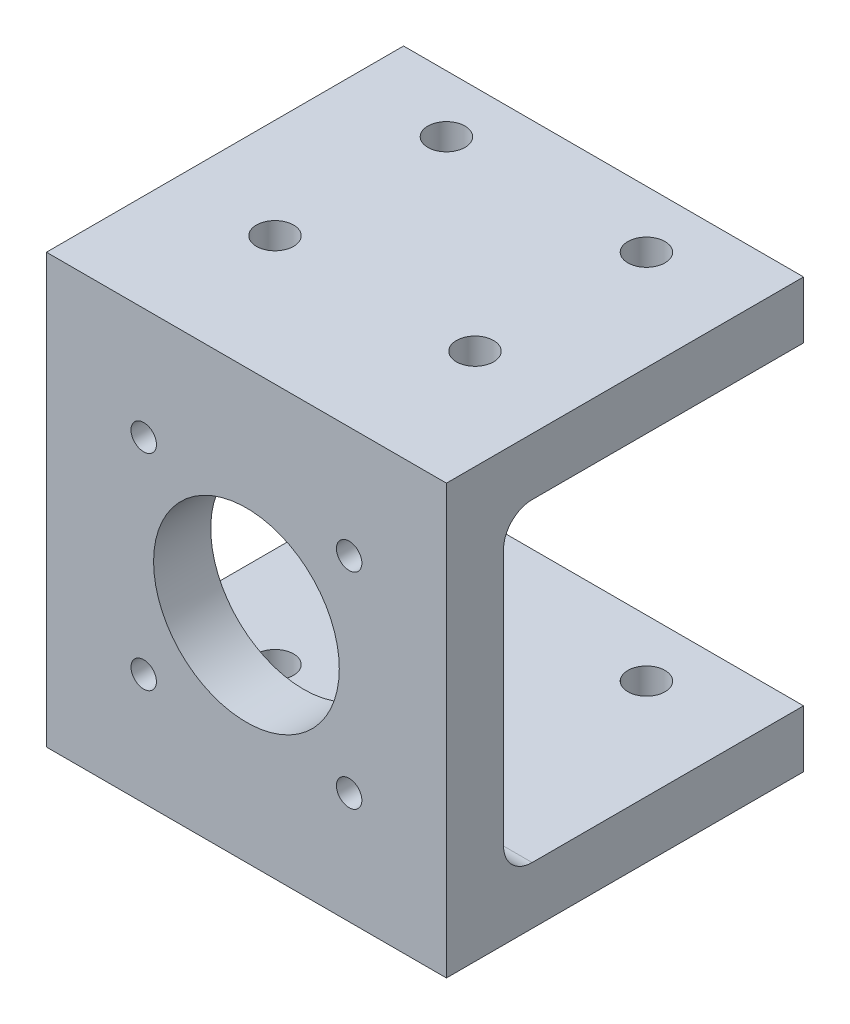
SolidWorks part; units mm, degrees
material "ABS"
ref_plane "Front Plane" through (0, 0, 0) normal (0, 0, 1) x (1, 0, 0)
ref_plane "Top Plane" through (0, 0, 0) normal (0, 1, 0) x (1, 0, 0)
ref_plane "Right Plane" through (0, 0, 0) normal (1, 0, 0) x (0, 0, -1)
sketch "Sketch1" plane through (0, 0, 0) normal (0, 0, 1) x (1, 0, 0)
  line L1 (-17.78, -19.05) -> (17.78, -19.05)
  line L2 (-17.78, -19.05) -> (-17.78, 19.05)
  line L3 (-17.78, 19.05) -> (17.78, 19.05)
  line L4 (17.78, -19.05) -> (17.78, 19.05)
  line L5 (-17.78, -19.05) -> (17.78, 19.05) construction
  line L6 (-17.78, 19.05) -> (17.78, -19.05) construction
  line L7 (-9.1313, -9.1313) -> (9.1313, -9.1313) construction
  line L8 (-9.1313, -9.1313) -> (-9.1313, 9.1313) construction
  line L9 (-9.1313, 9.1313) -> (9.1313, 9.1313) construction
  line L10 (9.1313, -9.1313) -> (9.1313, 9.1313) construction
  line L11 (-9.1313, -9.1313) -> (9.1313, 9.1313) construction
  line L12 (-9.1313, 9.1313) -> (9.1313, -9.1313) construction
  circle A0 centre (0, 0) radius 8.255
  circle A1 centre (-9.1313, 9.1313) radius 1.1303
  circle A2 centre (9.1313, 9.1313) radius 1.1303
  circle A3 centre (-9.1313, -9.1313) radius 1.1303
  circle A4 centre (9.1313, -9.1313) radius 1.1303
  point P0 (0, 0)
  dimension "D3" = 16.51
  dimension "D5" = 2.2606
  dimension "D1" = 38.1
  dimension "D2" = 35.56
  dimension "D4" = 18.2626
  dimension "D6" = 18.2626
extrude "Boss-Extrude with 4-40 Tap Drill Holes" add sketch "Sketch1" against normal mid plane 31.75
sketch "Sketch3" plane through (17.78, 0, 0) normal (1, 0, 0) x (0, 0, -1)
  line L0 (15.875, -19.05) -> (15.875, 19.05) construction
  line L1 (15.875, 13.97) -> (-10.795, 13.97)
  line L2 (15.875, 13.97) -> (15.875, -13.97)
  line L3 (15.875, -13.97) -> (-10.795, -13.97)
  line L4 (-10.795, 13.97) -> (-10.795, -13.97)
  line L5 (15.875, 19.05) -> (-15.875, 19.05) construction
  line L6 (15.875, -19.05) -> (-15.875, -19.05) construction
  line L7 (-15.875, -19.05) -> (-15.875, 19.05) construction
  dimension "D1" = 5.08
  dimension "D2" = 5.08
  dimension "D3" = 5.08
extrude "Cut-Extrude1" cut sketch "Sketch3" against normal up to next
fillet "Fillet1" radius 2.54 2 edges at (0, -13.97, 10.795) (0, 13.97, 10.795)
sketch "Sketch5" plane through (0, 19.05, 0) normal (0, 1, 0) x (1, 0, 0)
  line L4 (-17.78, 15.875) -> (-17.78, -8.255)
  line L5 (-17.78, 15.875) -> (-17.78, -8.255)
  line L6 (17.78, -8.255) -> (17.78, 15.875)
  line L7 (17.78, 15.875) -> (-17.78, 15.875)
  line L8 (-17.78, -8.255) -> (17.78, -8.255)
  line L9 (-17.78, -8.255) -> (17.78, -8.255)
  line L10 (17.78, -8.255) -> (17.78, 15.875)
  line L11 (17.78, 15.875) -> (-17.78, 15.875)
  circle A0 centre (-8.89, 10.795) radius 1.65
  circle A1 centre (8.89, 10.795) radius 1.65
  circle A2 centre (8.89, -4.445) radius 1.65
  circle A3 centre (-8.89, -4.445) radius 1.65
  dimension "D2" = 3.3
  dimension "D3" = 8.89
  dimension "D4" = 8.89
  dimension "D5" = 5.08
  dimension "D6" = 3.81
  dimension "D1" = 0
extrude "Clearance Holes for M3 Screw" cut sketch "Sketch5" against normal through all contours A0 | A3 | A2 | A1
